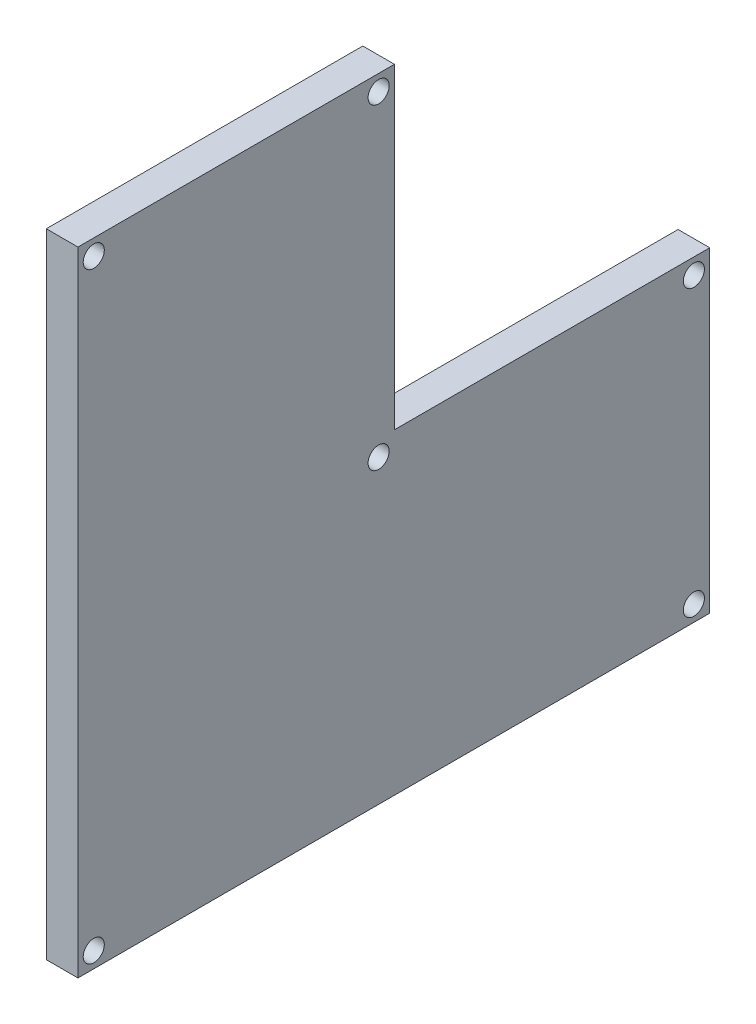
SolidWorks part; units mm, degrees
ref_plane "Plan de face" through (0, 0, 0) normal (0, 0, 1) x (1, 0, 0)
ref_plane "Plan de dessus" through (0, 0, 0) normal (0, 1, 0) x (1, 0, 0)
ref_plane "Plan de droite" through (0, 0, 0) normal (1, 0, 0) x (0, 0, -1)
sketch "Esquisse1" plane through (0, 0, 0) normal (1, 0, 0) x (0, 0, -1)
  line L1 (-15.1822, 19.3117) -> (14.8178, 19.3117)
  line L2 (-15.1822, 19.3117) -> (-15.1822, -10.6883)
  line L3 (-15.1822, -10.6883) -> (14.8178, -10.6883)
  line L4 (14.8178, 19.3117) -> (14.8178, -10.6883)
  line L5 (14.8178, -10.6883) -> (44.6978, -10.6883)
  line L6 (14.8178, -10.6883) -> (14.8178, -40.6883)
  line L7 (14.8178, -40.6883) -> (44.6978, -40.6883)
  line L8 (44.6978, -10.6883) -> (44.6978, -40.6883)
  line L9 (14.8178, -40.6883) -> (-15.1822, -40.6883)
  line L10 (14.8178, -40.6883) -> (14.8178, -10.6883)
  line L11 (14.8178, -10.6883) -> (-15.1822, -10.6883)
  line L12 (-15.1822, -40.6883) -> (-15.1822, -10.6883)
  dimension "D1" = 30
  dimension "D2" = 30
  dimension "D3" = 29.88
  dimension "D4" = 30
extrude "Boss.-Extru.1" add sketch "Esquisse1" along normal blind 3 contours L8 L5 L6 L7 | L12 L9 L6 L3 | L4 L1 L2 L3
sketch "Esquisse2" plane through (0, 0, 0) normal (-1, 0, 0) x (0, 0, 1)
  line L0 (-44.6978, -10.6883) -> (-44.6978, -40.6883) construction
  line L1 (-41.6978, -37.6883) -> (12.1822, -37.6883)
  line L2 (-41.6978, -37.6883) -> (-41.6978, -13.6883)
  line L3 (-41.6978, -13.6883) -> (12.1822, -13.6883)
  line L4 (12.1822, -37.6883) -> (12.1822, -13.6883)
  line L5 (12.1822, -13.6883) -> (-11.8178, -13.6883)
  line L6 (12.1822, -13.6883) -> (12.1822, 16.3117)
  line L7 (12.1822, 16.3117) -> (-11.8178, 16.3117)
  line L8 (-11.8178, -13.6883) -> (-11.8178, 16.3117)
  line L9 (-14.8178, -10.6883) -> (-44.6978, -10.6883) construction
  line L10 (-14.8178, 19.3117) -> (-14.8178, -10.6883) construction
  line L11 (15.1822, 19.3117) -> (-14.8178, 19.3117) construction
  line L12 (15.1822, -40.6883) -> (15.1822, 19.3117) construction
  line L13 (15.1822, -40.6883) -> (-44.6978, -40.6883) construction
  line L14 (-44.6978, -40.6883) -> (-41.6978, -37.6883)
  line L15 (-44.6978, -10.6883) -> (-41.6978, -13.6883)
  line L16 (-14.8178, -10.6883) -> (-11.8178, -13.6883)
  line L17 (-14.8178, 19.3117) -> (-11.8178, 16.3117)
  line L18 (12.1822, 16.3117) -> (15.1822, 19.3117)
  line L19 (12.1822, -37.6883) -> (15.1822, -40.6883)
  circle A0 centre (13.6822, -39.1883) radius 1
  circle A1 centre (13.6822, 17.8117) radius 1
  circle A2 centre (-13.3178, 17.8117) radius 1
  circle A3 centre (-13.3178, -12.1883) radius 1
  circle A4 centre (-43.1978, -12.1883) radius 1
  circle A5 centre (-43.1978, -39.1883) radius 1
  dimension "D1" = 3
  dimension "D2" = 3
  dimension "D3" = 3
  dimension "D4" = 3
  dimension "D5" = 3
  dimension "D6" = 3
extrude "Enlèv. mat.-Extru.1" cut sketch "Esquisse2" against normal blind 3 contours L14 A5 | L14 A5 | L15 A4 | L15 A4 | L16 A3 | L16 A3 | L17 A2 | L17 A2 | L18 A1 | L18 A1 | L19 A0 | L19 A0
